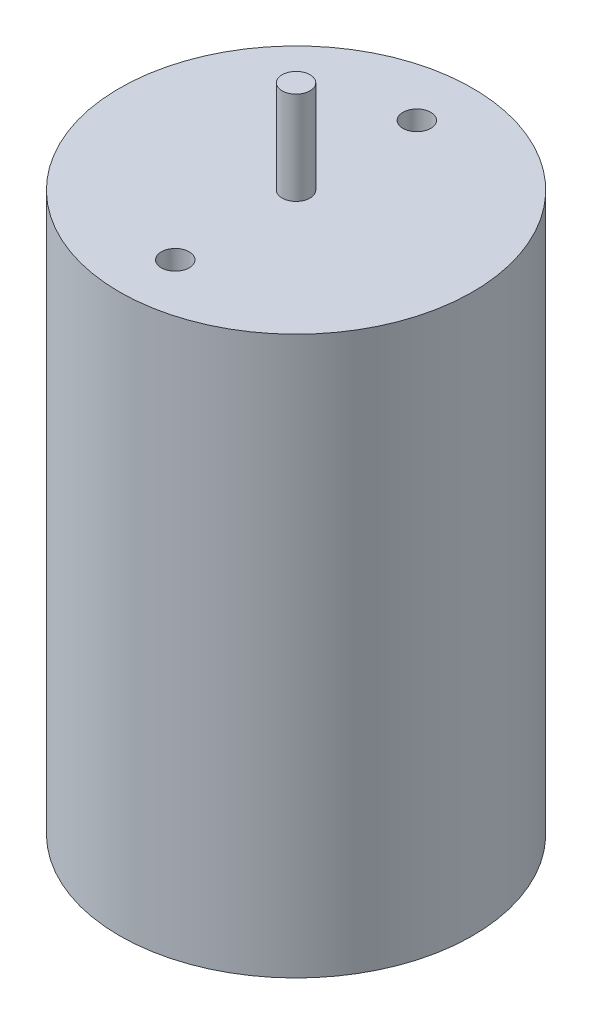
SolidWorks part; units mm, degrees
ref_plane "Front Plane" through (0, 0, 0) normal (0, 0, 1) x (1, 0, 0)
ref_plane "Top Plane" through (0, 0, 0) normal (0, 1, 0) x (1, 0, 0)
ref_plane "Right Plane" through (0, 0, 0) normal (1, 0, 0) x (0, 0, -1)
sketch "Sketch1" plane through (0, 0, 0) normal (0, 1, 0) x (1, 0, 0)
  circle A0 centre (0, 0) radius 19
  dimension "D1" = 38
extrude "Boss-Extrude1" add sketch "Sketch1" along normal blind 60
sketch "Sketch2" plane through (0, 60, 0) normal (0, 1, 0) x (1, 0, 0)
  circle A0 centre (0, 0) radius 1.5
  dimension "D1" = 3
extrude "Boss-Extrude2" add sketch "Sketch2" along normal blind 10
sketch "Sketch3" plane through (0, 60, 0) normal (0, 1, 0) x (1, 0, 0)
  line L0 (0, 19) -> (0, -19) construction
  circle A0 centre (0, 0) radius 19 construction
  circle A1 centre (0, -13) radius 1.5
  circle A2 centre (0, 13) radius 1.5
  point P9 (0, 0)
  dimension "D1" = 13
  dimension "D3" = 3
  dimension "D2" = 13
extrude "Cut-Extrude1" cut sketch "Sketch3" against normal blind 10
equation "\"motor_diameter\"= 38mm"
equation "\"D1@Sketch1\"=\"motor_diameter\""
equation "\"motor_length\"= 60mm"
equation "\"shaft_diameter\"= 5mm"
equation "\"D1@Boss-Extrude1\"=\"motor_length\""
equation "\"shaft_length\"= 10mm"
equation "\"D1@Boss-Extrude2\"=\"shaft_length\""
